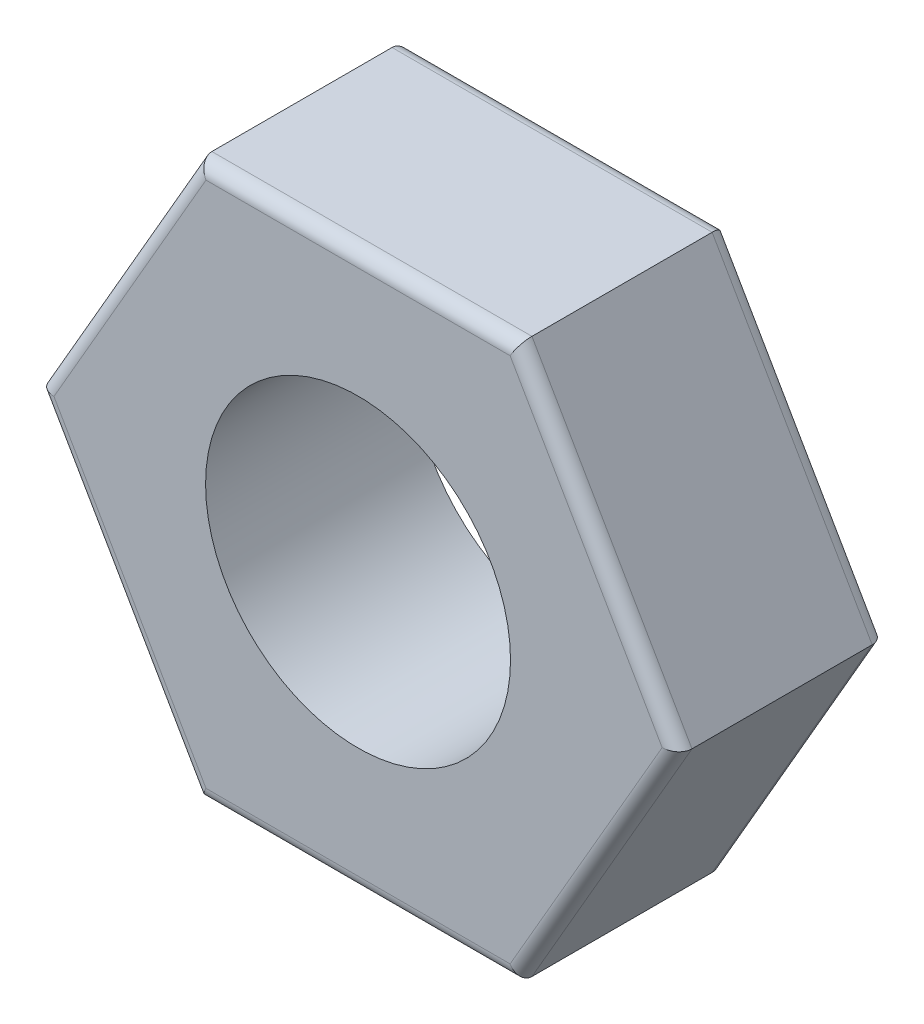
SolidWorks part; units mm, degrees
ref_plane "前视基准面" through (0, 0, 0) normal (0, 0, 1) x (1, 0, 0)
ref_plane "上视基准面" through (0, 0, 0) normal (0, 1, 0) x (1, 0, 0)
ref_plane "右视基准面" through (0, 0, 0) normal (1, 0, 0) x (0, 0, -1)
sketch "草图1" plane through (0, 0, 0) normal (0, 0, 1) x (1, 0, 0)
  line L1 (11.547, -20) -> (23.094, 0)
  line L2 (23.094, 0) -> (11.547, 20)
  line L3 (11.547, 20) -> (-11.547, 20)
  line L4 (-11.547, 20) -> (-23.094, 0)
  line L5 (-23.094, 0) -> (-11.547, -20)
  line L6 (-11.547, -20) -> (11.547, -20)
  circle A0 centre (0, 0) radius 20 construction
  dimension "D1" = 40
extrude "凸台-拉伸3" add sketch "草图1" along normal blind 15
fillet "圆角3" radius 1 12 edges at (17.3205, 10, 0) (17.3205, -10, 0) (0, -20, 0) (-17.3205, -10, 0) (-17.3205, 10, 0) (0, 20, 0) (-17.3205, 10, 15) (-17.3205, -10, 15) (0, -20, 15) (17.3205, -10, 15) (17.3205, 10, 15) (0, 20, 15)
sketch "草图4" plane through (0, 0, 15) normal (0, 0, 1) x (1, 0, 0)
  circle A0 centre (0, 0) radius 11
  dimension "D1" = 22
extrude "切除-拉伸1" cut sketch "草图4" against normal through all
